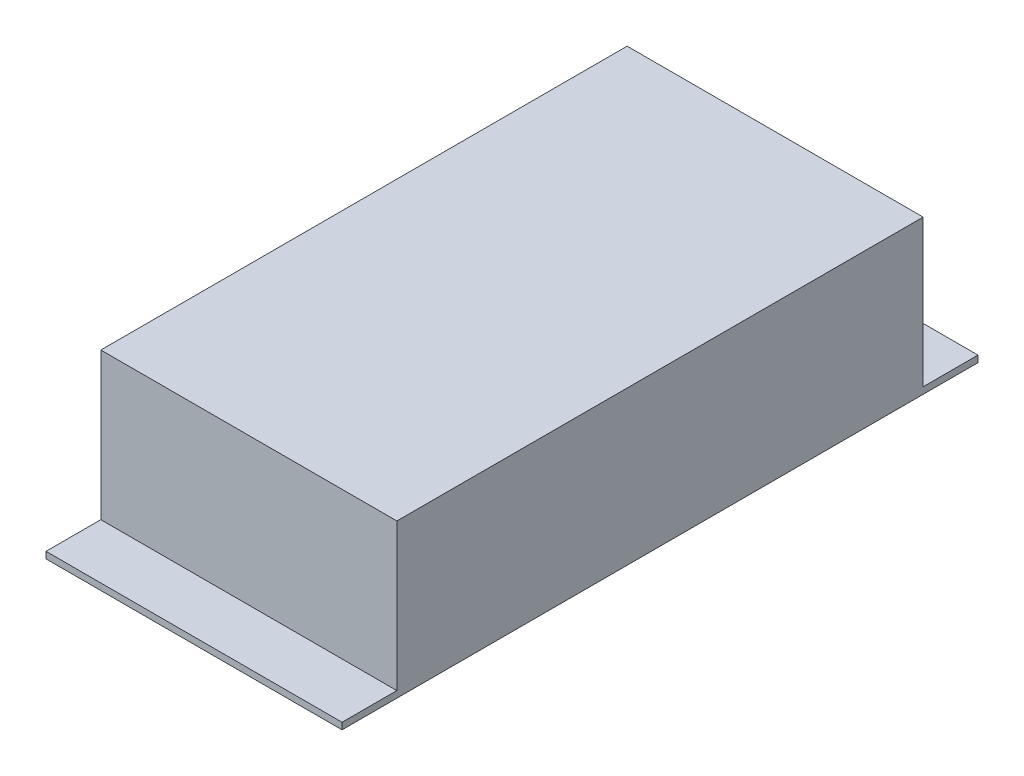
SolidWorks part; units mm, degrees
ref_plane "Front Plane" through (0, 0, 0) normal (0, 0, 1) x (1, 0, 0)
ref_plane "Top Plane" through (0, 0, 0) normal (0, 1, 0) x (1, 0, 0)
ref_plane "Right Plane" through (0, 0, 0) normal (1, 0, 0) x (0, 0, -1)
sketch "Sketch2" plane through (0, 0, 0) normal (0, 1, 0) x (1, 0, 0)
  line L1 (-67.5, 145) -> (67.5, 145)
  line L2 (-67.5, 145) -> (-67.5, -145)
  line L3 (-67.5, -145) -> (67.5, -145)
  line L4 (67.5, 145) -> (67.5, -145)
  line L5 (-67.5, 145) -> (67.5, -145) construction
  line L6 (-67.5, -145) -> (67.5, 145) construction
  point P0 (0, 0)
  dimension "D1" = 135
  dimension "D2" = 290
extrude "Boss-Extrude1" add sketch "Sketch2" along normal blind 70
sketch "Sketch4" plane through (0, 70, 0) normal (0, 1, 0) x (1, 0, 0)
  line L0 (67.5, -145) -> (67.5, 145) construction
  line L1 (-67.5, -145) -> (67.5, -145)
  line L2 (-67.5, -145) -> (-67.5, -120)
  line L3 (-67.5, -120) -> (67.5, -120)
  line L4 (67.5, -145) -> (67.5, -120)
  line L5 (-67.5, 145) -> (-67.5, -145) construction
  line L6 (67.5, 145) -> (-67.5, 145)
  line L7 (67.5, 145) -> (67.5, 120)
  line L8 (67.5, 120) -> (-67.5, 120)
  line L9 (-67.5, 145) -> (-67.5, 120)
  dimension "D1" = 25
  dimension "D2" = 25
extrude "Cut-Extrude1" cut sketch "Sketch4" against normal blind 67
